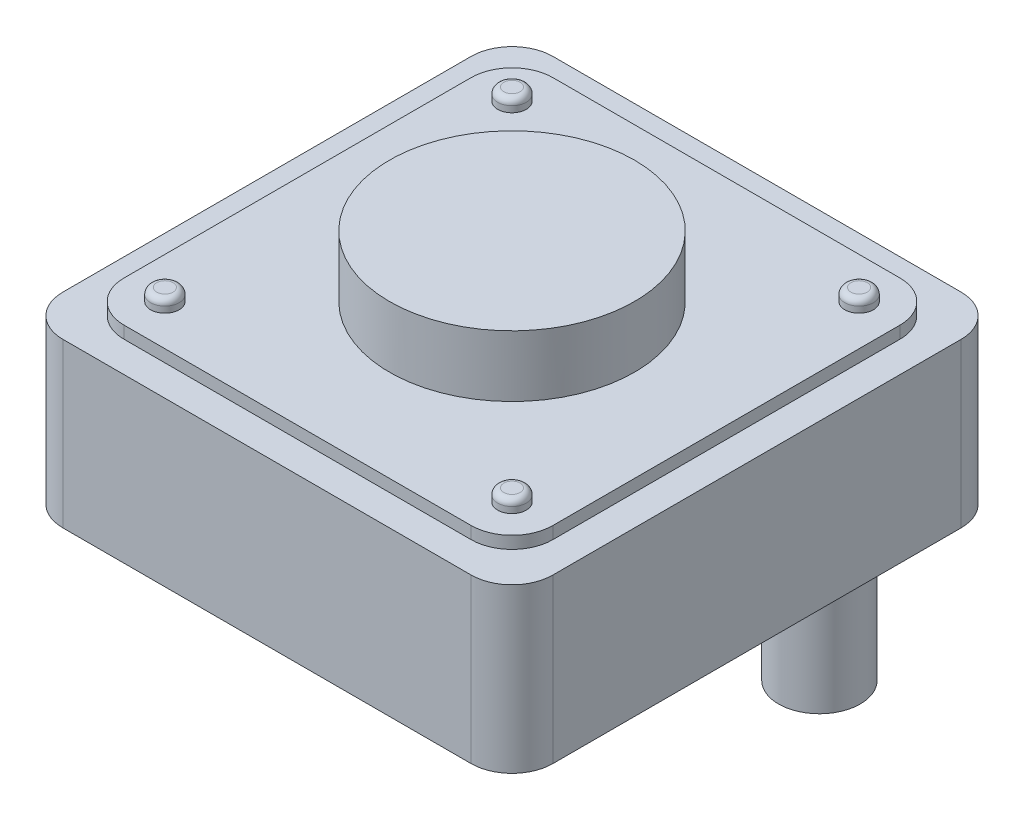
SolidWorks part; units mm, degrees
ref_plane "Front Plane" through (0, 0, 0) normal (0, 0, 1) x (1, 0, 0)
ref_plane "Top Plane" through (0, 0, 0) normal (0, 1, 0) x (1, 0, 0)
ref_plane "Right Plane" through (0, 0, 0) normal (1, 0, 0) x (0, 0, -1)
sketch "Sketch1" plane through (0, 0, 0) normal (0, 1, 0) x (1, 0, 0)
  line L0 (-34.069, 0) -> (38.8966, 0) construction
  line L1 (0, -25.0345) -> (0, 24.2069) construction
  line L3 (-5, 6) -> (5, 6)
  line L4 (-6, 5) -> (-6, -5)
  line L5 (-5, -6) -> (5, -6)
  line L6 (6, 5) -> (6, -5)
  line L7 (-6, 6) -> (6, -6) construction
  line L8 (-6, -6) -> (6, 6) construction
  arc A0 (-6, -5) -> (-5, -6) centre (-5, -5) ccw
  arc A1 (5, -6) -> (6, -5) centre (5, -5) ccw
  arc A2 (5, 6) -> (6, 5) centre (5, 5) cw
  arc A3 (-5, 6) -> (-6, 5) centre (-5, 5) ccw
  point P5 (0, 0)
  dimension "D3" = 1
  dimension "D1" = 12
  dimension "D2" = 12
extrude "Boss-Extrude1" add sketch "Sketch1" along normal blind 4
sketch "Sketch2" plane through (0, 4, 0) normal (0, 1, 0) x (1, 0, 0)
  line L1 (-4.25, 5.25) -> (4.25, 5.25)
  line L2 (-5.25, 4.25) -> (-5.25, -4.25)
  line L3 (-4.25, -5.25) -> (4.25, -5.25)
  line L4 (5.25, 4.25) -> (5.25, -4.25)
  line L5 (-5.25, 5.25) -> (5.25, -5.25) construction
  line L6 (-5.25, -5.25) -> (5.25, 5.25) construction
  arc A0 (4.25, 5.25) -> (5.25, 4.25) centre (4.25, 4.25) cw
  arc A1 (4.25, -5.25) -> (5.25, -4.25) centre (4.25, -4.25) ccw
  arc A2 (-5.25, -4.25) -> (-4.25, -5.25) centre (-4.25, -4.25) ccw
  arc A3 (-4.25, 5.25) -> (-5.25, 4.25) centre (-4.25, 4.25) ccw
  point P0 (0, 0)
  dimension "D3" = 1
  dimension "D1" = 10.5
  dimension "D2" = 10.5
extrude "Boss-Extrude2" add sketch "Sketch2" along normal blind 0.3
sketch "Sketch3" plane through (0, 4.3, 0) normal (0, 1, 0) x (1, 0, 0)
  line L0 (-8.4181, 0) -> (8.1522, 0) construction
  line L1 (0, -7.2175) -> (0, 8.1841) construction
  circle A0 centre (4.25, 4.25) radius 0.35
  circle A1 centre (4.25, -4.25) radius 0.35
  circle A2 centre (-4.25, -4.25) radius 0.35
  circle A3 centre (-4.25, 4.25) radius 0.35
extrude "Boss-Extrude3" add sketch "Sketch3" along normal blind 0.3
fillet "Fillet2" radius 0.15 1 edges at (-4.25, 4.6, -4.6)
fillet "Fillet3" radius 0.15 3 edges at (-4.25, 4.6, 4.6) (4.25, 4.6, 3.9) (4.25, 4.6, -3.9)
sketch "Sketch4" plane through (0, 4.3, 0) normal (0, 1, 0) x (1, 0, 0)
  circle A0 centre (0, 0) radius 3
  dimension "D1" = 6
extrude "Boss-Extrude4" add sketch "Sketch4" along normal blind 1.5
sketch "Sketch5" plane through (0, 0, 0) normal (0, -1, 0) x (1, 0, 0)
  line L0 (0, -7.6604) -> (0, 8.216) construction
  circle A0 centre (2.5, -5.0279) radius 1
  circle A1 centre (-2.5, -5.0279) radius 1
  dimension "D1" = 2
  dimension "D2" = 2.5
extrude "Boss-Extrude5" add sketch "Sketch5" along normal blind 5
